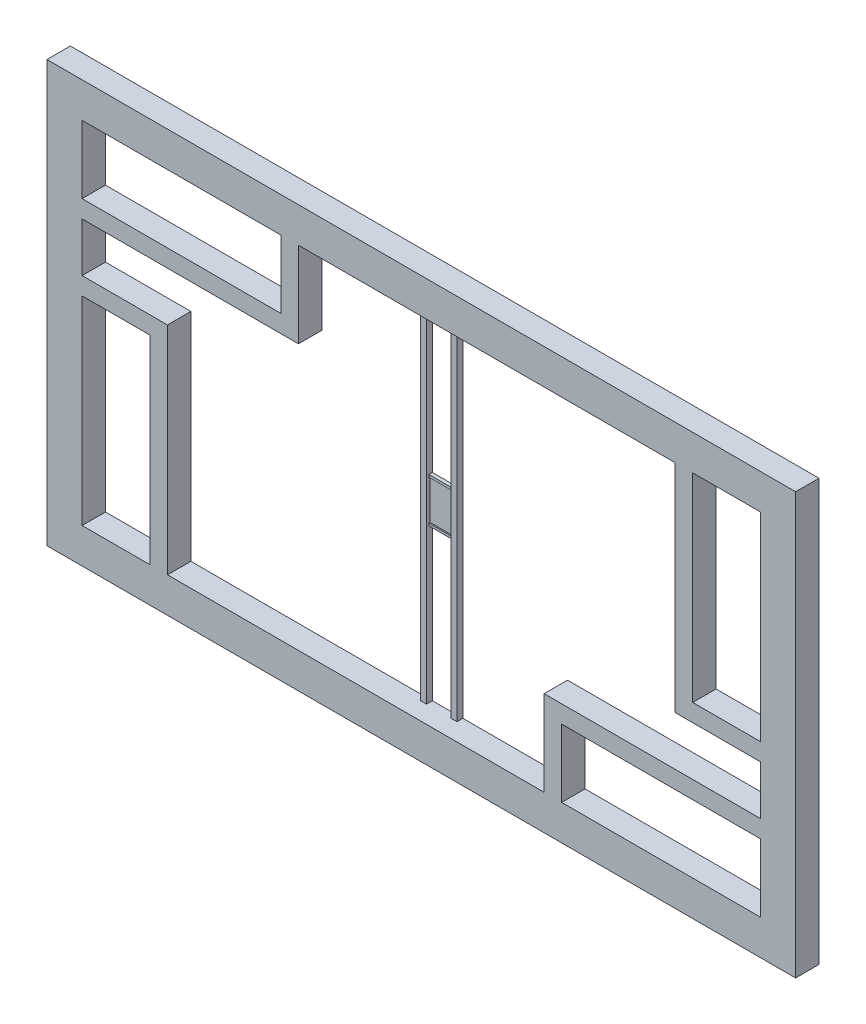
SolidWorks part; units mm, degrees
material "Eucalipto"
ref_plane "Plano frontal" through (0, 0, 0) normal (0, 0, 1) x (1, 0, 0)
ref_plane "Plano superior" through (0, 0, 0) normal (0, 1, 0) x (1, 0, 0)
ref_plane "Plano direito" through (0, 0, 0) normal (1, 0, 0) x (0, 0, -1)
sketch "Esboço1" plane through (0, 0, 0) normal (0, 0, 1) x (1, 0, 0)
  line L0 (215, 330) -> (537, 330)
  line L1 (0, 0) -> (640, 0)
  line L2 (0, 0) -> (0, 360)
  line L3 (0, 360) -> (640, 360)
  line L4 (640, 0) -> (640, 360)
  line L5 (30, 330) -> (200, 330)
  line L6 (30, 330) -> (30, 272)
  line L7 (30, 30) -> (88, 30)
  line L8 (610, 330) -> (610, 160)
  line L10 (200, 330) -> (200, 272)
  line L11 (200, 257) -> (215, 257)
  line L12 (215, 330) -> (215, 257)
  line L13 (200, 257) -> (30, 257)
  line L15 (200, 272) -> (30, 272)
  line L17 (30, 215) -> (88, 215)
  line L19 (30, 200) -> (88, 200)
  line L21 (88, 215) -> (103, 215)
  line L22 (88, 200) -> (88, 30)
  line L24 (103, 215) -> (103, 30)
  line L26 (425, 88) -> (425, 30)
  line L28 (440, 88) -> (440, 30)
  line L29 (440, 88) -> (610, 88)
  line L30 (425, 88) -> (425, 103)
  line L31 (425, 103) -> (610, 103)
  line L34 (537, 330) -> (537, 160)
  line L36 (552, 330) -> (552, 160)
  line L37 (552, 160) -> (610, 160)
  line L38 (537, 160) -> (537, 145)
  line L39 (537, 145) -> (610, 145)
  line L41 (30, 257) -> (30, 215)
  line L42 (103, 30) -> (425, 30)
  line L43 (30, 200) -> (30, 30)
  line L44 (440, 30) -> (610, 30)
  line L45 (610, 88) -> (610, 30)
  line L46 (610, 145) -> (610, 103)
  line L47 (552, 330) -> (610, 330)
  point P37 (103, 122.5)
  point P38 (425, 59)
  point P39 (552, 245)
  dimension "D1" = 640
  dimension "D2" = 360
  dimension "D3" = 30
  dimension "D4" = 30
  dimension "D5" = 30
  dimension "D6" = 30
  dimension "D7" = 15
  dimension "D8" = 15
  dimension "D9" = 15
  dimension "D10" = 15
  dimension "D11" = 15
  dimension "D12" = 15
  dimension "D13" = 15
  dimension "D14" = 15
  dimension "D15" = 170
  dimension "D16" = 58
  dimension "D17" = 170
  dimension "D18" = 58
  dimension "D19" = 170
  dimension "D20" = 58
  dimension "D21" = 170
  dimension "D22" = 58
  dimension "D23" = 15
  dimension "D24" = 15
  dimension "D25" = 15
  dimension "D26" = 15
extrude "Ressalto-extrusão1" add sketch "Esboço1" along normal blind 20
sketch "Sketch1" plane through (0, 330, 0) normal (0, -1, 0) x (1, 0, 0)
  line L0 (537, 0) -> (215, 0) construction
  line L1 (304.5, 0) -> (309.5, 0)
  line L2 (304.5, 0) -> (304.5, 5)
  line L3 (304.5, 5) -> (309.5, 5)
  line L4 (309.5, 0) -> (309.5, 5)
  line L5 (30, 20) -> (30, 0) construction
  line L7 (335.5, 0) -> (330.5, 0)
  line L8 (335.5, 0) -> (335.5, 5)
  line L9 (335.5, 5) -> (330.5, 5)
  line L10 (330.5, 0) -> (330.5, 5)
  dimension "D1" = 5
  dimension "D2" = 5
  dimension "D3" = 274.5
  dimension "D4" = 5
  dimension "D5" = 5
  dimension "D6" = 21
extrude "Boss-Extrude1" add sketch "Sketch1" along normal up to surface (300 mm away) up to face at (264, 30, 10)
sketch "Sketch2" plane through (309.5, 0, 0) normal (1, 0, 0) x (0, 0, -1)
  line L0 (0, 30) -> (0, 330) construction
  line L1 (0, 163) -> (-2, 163)
  line L2 (0, 163) -> (0, 197)
  line L3 (0, 197) -> (-2, 197)
  line L4 (-2, 163) -> (-2, 197)
  line L5 (-5, 30) -> (0, 30) construction
  dimension "D1" = 34
  dimension "D2" = 2
  dimension "D3" = 133
extrude "Boss-Extrude2" add sketch "Sketch2" along normal up to surface (21 mm away) up to face at (330.5, 180, 2.5)
sketch "Sketch3" plane through (309.5, 0, 0) normal (1, 0, 0) x (0, 0, -1)
  line L1 (0, 197) -> (-3, 197)
  line L2 (0, 197) -> (0, 199)
  line L3 (0, 199) -> (-3, 199)
  line L4 (-3, 197) -> (-3, 199)
  line L5 (0, 163) -> (-3, 163)
  line L6 (0, 163) -> (0, 161)
  line L7 (0, 161) -> (-3, 161)
  line L8 (-3, 163) -> (-3, 161)
  dimension "D1" = 3
  dimension "D2" = 2
  dimension "D3" = 2
extrude "Boss-Extrude3" add sketch "Sketch3" along normal up to surface (21 mm away) up to face at (330.5, 180, 1.75)
